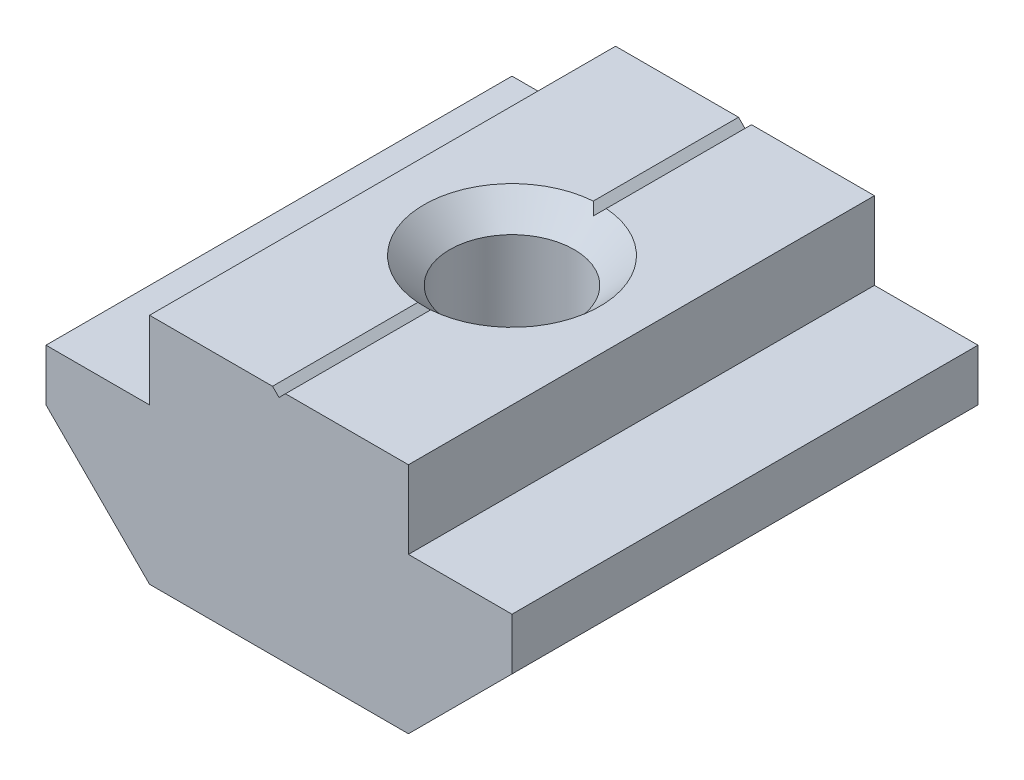
SolidWorks part; units mm, degrees
ref_plane "Front plane" through (0, 0, 0) normal (0, 0, 1) x (1, 0, 0)
ref_plane "Top plane" through (0, 0, 0) normal (0, 1, 0) x (1, 0, 0)
ref_plane "Right plane" through (0, 0, 0) normal (1, 0, 0) x (0, 0, -1)
sketch "Эскиз1" plane through (0, 0, 0) normal (0, 0, 1) x (1, 0, 0)
  line L0 (0, 0) -> (0, 9.7116) construction
  line L1 (-5, 0) -> (-9, 4)
  line L2 (-9, 4) -> (-9, 6)
  line L3 (-9, 6) -> (-5, 6)
  line L4 (-5, 6) -> (-5, 9)
  line L5 (-5, 9) -> (-0.25, 9)
  line L6 (-0.25, 9) -> (0, 8.75)
  line L7 (9, 4) -> (9, 6)
  line L8 (5, 0) -> (9, 4)
  line L9 (0.25, 9) -> (0, 8.75)
  line L10 (5, 9) -> (0.25, 9)
  line L11 (5, 6) -> (5, 9)
  line L12 (9, 6) -> (5, 6)
  line L13 (-5, 0) -> (5, 0)
  dimension "D1" = 9
  dimension "D2" = 10
  dimension "D3" = 3
  dimension "D4" = 2
  dimension "D5" = 18
  dimension "D6" = 45
  dimension "D7" = 0.5
extrude "Extruded 1" add sketch "Эскиз1" along normal blind 18
sketch "Эскиз2" plane through (0, 0, 0) normal (1, 0, 0) x (0, 0, -1)
  line L0 (-9, 0) -> (-9, 9)
  line L1 (-18, 0) -> (0, 0) construction
  line L2 (-18, 9) -> (0, 9) construction
  line L3 (-9, 9) -> (-5.6, 9)
  line L4 (-5.6, 9) -> (-6.6, 8)
  line L5 (-6.6, 8) -> (-6.6, 1)
  line L6 (-6.6, 1) -> (-5.6, 0)
  line L7 (-5.6, 0) -> (-9, 0)
  dimension "D1" = 45
  dimension "D2" = 2.4
  dimension "D3" = 3.4
revolve "Revolved Cut 1" cut sketch "Эскиз2" angle 360 about L0
cosmetic thread "резьба" parameters "D2"=6
equation "\"Thread_length@ThreadCosmetic\" =  (  ( sgn (  ( \"Length@BodySke\" - \"Advance@BodySke\" *  3.0  - \"Head_ht@BodySke\" )  - \"Thread_nom@BodySke\" )  - 1 )  *  (  ( \"Length@BodySke\" - \"Advance@BodySke\" *  3.0  - \"Head_ht@BodySke\" )  - \"Thread_nom@BodySke\" )  )  /  - 2 + \"Thread_nom@BodySke\""
equation "\"Num_threads\"=  int ( \"Thread_length@ThreadCosmetic\" / \"Advance@BodySke\" +  0.999  )  +  1"
